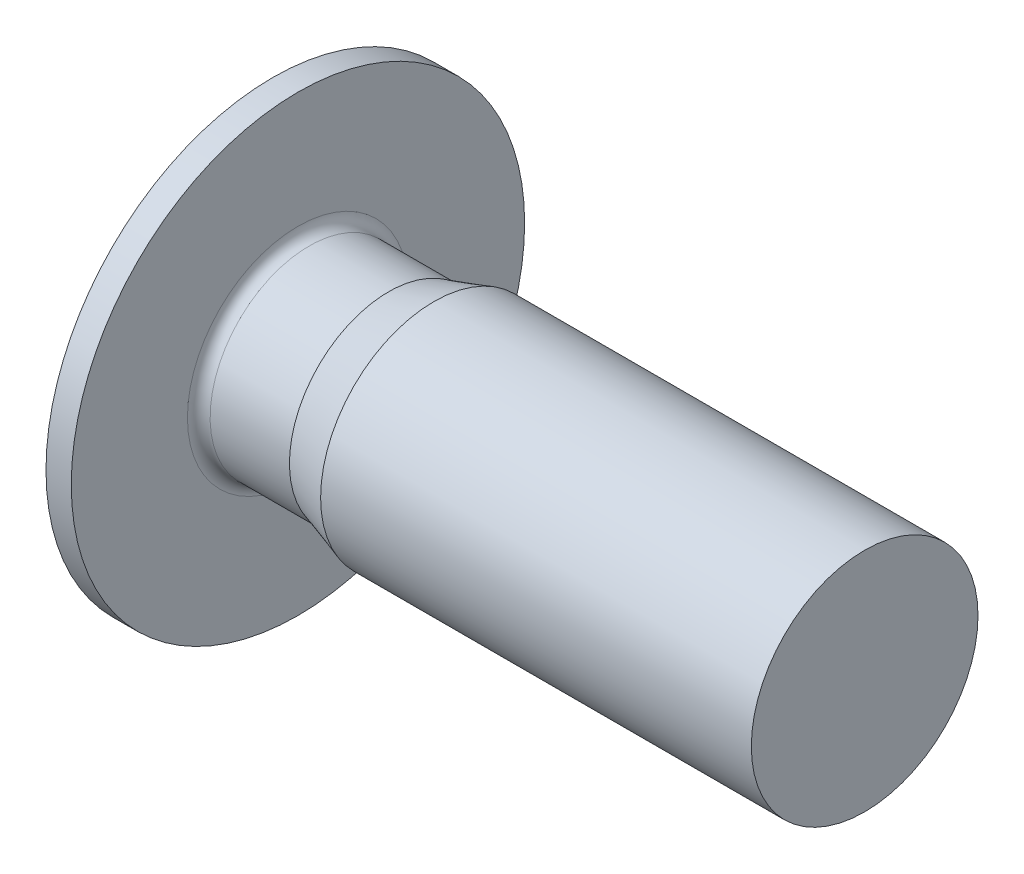
SolidWorks part; units mm, degrees
material "SCM435"
ref_plane "Front Plane" through (0, 0, 0) normal (0, 0, 1) x (1, 0, 0)
ref_plane "Top Plane" through (0, 0, 0) normal (0, 1, 0) x (1, 0, 0)
ref_plane "Right Plane" through (0, 0, 0) normal (1, 0, 0) x (0, 0, -1)
sketch "Sketch1" plane through (0, 0, 0) normal (0, 0, 1) x (1, 0, 0)
  line L0 (-0.5, 0) -> (5, 0) construction
  line L1 (-0.5, 0) -> (-0.5, 1.52)
  line L2 (-0.2229, 2) -> (0, 2)
  line L3 (0, 2) -> (0, 0.875)
  line L4 (1.2, 1) -> (5, 1)
  line L5 (5, 1) -> (5, 0)
  line L6 (5, 0) -> (-0.5, 0)
  line L7 (1.2, 1) -> (0.8, 0.875)
  line L8 (0.8, 0.875) -> (0, 0.875)
  line L9 (-0.2229, 2) -> (-0.5, 1.52)
  line L10 (-0.5, 0) -> (5, 0) construction
  dimension "A" = 4
  dimension "M" = 2
  dimension "L" = 5
  dimension "E" = 0.5
  dimension "FIX_1" = 30
  dimension "MSM_1" = 3.04
  dimension "MSM_2" = 1.75
  dimension "MSM_3" = 0.4
  dimension "E_s" = 1.2
revolve "Revolve1" add sketch "Sketch1" angle 360 about L0
cosmetic thread "Thread1" parameters "ATL_1"=3.8, "ATD"=1.567
fillet "Fillet1" radius 0.1 1 edges at (0, -0.875, 0)
sketch "Sketch2" plane through (-0.5, 0, 0) normal (-1, 0, 0) x (0, 0, 1)
  line L1 (0, 0.7506) -> (-0.65, 0.3753)
  line L2 (-0.65, 0.3753) -> (-0.65, -0.3753)
  line L3 (-0.65, -0.3753) -> (0, -0.7506)
  line L4 (0, -0.7506) -> (0.65, -0.3753)
  line L5 (0.65, -0.3753) -> (0.65, 0.3753)
  line L6 (0.65, 0.3753) -> (0, 0.7506)
  circle A0 centre (0, 0) radius 0.65 construction
  dimension "B" = 1.3
extrude "Cut-Extrude1" cut sketch "Sketch2" against normal blind 1.2
sketch "Sketch3" plane through (0, 0, 0) normal (0, 0, 1) x (1, 0, 0)
  line L0 (0.7, 0) -> (1.0906, 0) construction
  line L1 (0.7, 0) -> (0.7, 0.65)
  line L2 (0.7, 0.65) -> (1.0906, 0)
  line L3 (1.0906, 0) -> (0.7, 0)
  line L5 (0.7, 0.3753) -> (0.7, -0.3753) construction
  dimension "FIX_3" = 59
  dimension "B" = 1.3
revolve "Cut-Revolve1" cut sketch "Sketch3" angle 360 about L0
equation "\"ATL_1@Thread1\" = \"L@Sketch1\" - \"E_s@Sketch1\""
